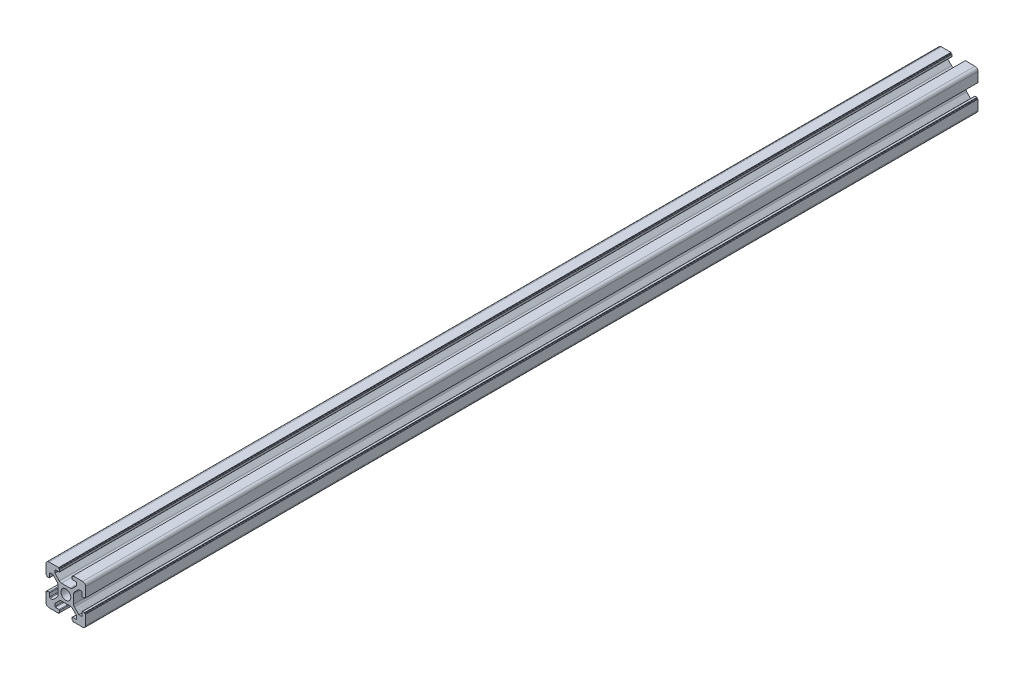
SolidWorks part; units mm, degrees
ref_plane "前视基准面" through (0, 0, 0) normal (0, 0, 1) x (1, 0, 0)
ref_plane "上视基准面" through (0, 0, 0) normal (0, 1, 0) x (1, 0, 0)
ref_plane "右视基准面" through (0, 0, 0) normal (1, 0, 0) x (0, 0, -1)
sketch "草图1" plane through (0, 0, 0) normal (0, 0, 1) x (1, 0, 0)
  line L0 (4.216, 3.2442) -> (6.4367, 5.4649)
  line L1 (6.4367, 5.4649) -> (7.7767, 5.4649)
  line L2 (8.0767, 5.1649) -> (8.0767, 3.3649)
  line L3 (8.3767, 3.0649) -> (9.3767, 3.0649)
  line L4 (9.3767, 3.0649) -> (9.3767, 3.3649)
  line L5 (9.5767, 3.5649) -> (9.8767, 3.5649)
  line L6 (9.8767, 3.5649) -> (9.8767, 8.4649)
  line L7 (8.3767, 9.9649) -> (3.4767, 9.9649)
  line L8 (3.4767, 9.9649) -> (3.4767, 9.6649)
  line L9 (3.2767, 9.4649) -> (2.9767, 9.4649)
  line L10 (2.9767, 9.4649) -> (2.9767, 8.4649)
  line L11 (3.2767, 8.1649) -> (5.0767, 8.1649)
  line L12 (5.3767, 7.8649) -> (5.3767, 6.5249)
  line L13 (5.3767, 6.5249) -> (3.156, 4.3042)
  line L14 (2.0953, 3.8649) -> (-2.342, 3.8649)
  line L15 (-3.4027, 4.3042) -> (-5.6233, 6.5249)
  line L16 (-5.6233, 6.5249) -> (-5.6233, 7.8649)
  line L17 (-5.3233, 8.1649) -> (-3.5233, 8.1649)
  line L18 (-3.2233, 8.4649) -> (-3.2233, 9.4649)
  line L19 (-3.2233, 9.4649) -> (-3.5233, 9.4649)
  line L20 (-3.7233, 9.6649) -> (-3.7233, 9.9649)
  line L21 (-3.7233, 9.9649) -> (-8.6233, 9.9649)
  line L22 (-10.1233, 8.4649) -> (-10.1233, 3.5649)
  line L23 (-10.1233, 3.5649) -> (-9.8233, 3.5649)
  line L24 (-9.6233, 3.3649) -> (-9.6233, 3.0649)
  line L25 (-9.6233, 3.0649) -> (-8.6233, 3.0649)
  line L26 (-8.3233, 3.3649) -> (-8.3233, 5.1649)
  line L27 (-8.0233, 5.4649) -> (-6.6833, 5.4649)
  line L28 (-6.6833, 5.4649) -> (-4.4627, 3.2442)
  line L29 (-4.0233, 2.1836) -> (-4.0233, -2.2538)
  line L30 (-4.4627, -3.3144) -> (-6.6833, -5.5351)
  line L31 (-6.6833, -5.5351) -> (-8.0233, -5.5351)
  line L32 (-8.3233, -5.2351) -> (-8.3233, -3.4351)
  line L33 (-8.6233, -3.1351) -> (-9.6233, -3.1351)
  line L34 (-9.6233, -3.1351) -> (-9.6233, -3.4351)
  line L35 (-9.8233, -3.6351) -> (-10.1233, -3.6351)
  line L36 (-10.1233, -3.6351) -> (-10.1233, -8.5351)
  line L37 (-8.6233, -10.0351) -> (-3.7233, -10.0351)
  line L38 (-3.7233, -10.0351) -> (-3.7233, -9.7351)
  line L39 (-3.5233, -9.5351) -> (-3.2233, -9.5351)
  line L40 (-3.2233, -9.5351) -> (-3.2233, -8.5351)
  line L41 (-3.5233, -8.2351) -> (-5.3233, -8.2351)
  line L42 (-5.6233, -7.9351) -> (-5.6233, -6.5951)
  line L43 (-5.6233, -6.5951) -> (-3.4027, -4.3744)
  line L44 (-2.342, -3.9351) -> (2.0953, -3.9351)
  line L45 (3.156, -4.3744) -> (5.3767, -6.5951)
  line L46 (5.3767, -6.5951) -> (5.3767, -7.9351)
  line L47 (5.0767, -8.2351) -> (3.2767, -8.2351)
  line L48 (2.9767, -8.5351) -> (2.9767, -9.5351)
  line L49 (2.9767, -9.5351) -> (3.2767, -9.5351)
  line L50 (3.4767, -9.7351) -> (3.4767, -10.0351)
  line L51 (3.4767, -10.0351) -> (8.3767, -10.0351)
  line L52 (9.8767, -8.5351) -> (9.8767, -3.6351)
  line L53 (9.8767, -3.6351) -> (9.5767, -3.6351)
  line L54 (9.3767, -3.4351) -> (9.3767, -3.1351)
  line L55 (9.3767, -3.1351) -> (8.3767, -3.1351)
  line L56 (8.0767, -3.4351) -> (8.0767, -5.2351)
  line L57 (7.7767, -5.5351) -> (6.4367, -5.5351)
  line L58 (6.4367, -5.5351) -> (4.216, -3.3144)
  line L59 (3.7767, -2.2538) -> (3.7767, 2.1836)
  circle A0 centre (-0.1233, -0.0351) radius 2.5
  arc A1 (8.0767, 5.1649) -> (7.7767, 5.4649) centre (7.7767, 5.1649) ccw
  arc A2 (8.0767, 3.3649) -> (8.3767, 3.0649) centre (8.3767, 3.3649) ccw
  arc A3 (9.5767, 3.5649) -> (9.3767, 3.3649) centre (9.5767, 3.3649) ccw
  arc A4 (9.8767, 8.4649) -> (8.3767, 9.9649) centre (8.3767, 8.4649) ccw
  arc A5 (3.2767, 9.4649) -> (3.4767, 9.6649) centre (3.2767, 9.6649) ccw
  arc A6 (2.9767, 8.4649) -> (3.2767, 8.1649) centre (3.2767, 8.4649) ccw
  arc A7 (5.3767, 7.8649) -> (5.0767, 8.1649) centre (5.0767, 7.8649) ccw
  arc A8 (2.0953, 3.8649) -> (3.156, 4.3042) centre (2.0953, 5.3649) ccw
  arc A9 (-3.4027, 4.3042) -> (-2.342, 3.8649) centre (-2.342, 5.3649) ccw
  arc A10 (-5.3233, 8.1649) -> (-5.6233, 7.8649) centre (-5.3233, 7.8649) ccw
  arc A11 (-3.5233, 8.1649) -> (-3.2233, 8.4649) centre (-3.5233, 8.4649) ccw
  arc A12 (-3.7233, 9.6649) -> (-3.5233, 9.4649) centre (-3.5233, 9.6649) ccw
  arc A13 (-8.6233, 9.9649) -> (-10.1233, 8.4649) centre (-8.6233, 8.4649) ccw
  arc A14 (-9.6233, 3.3649) -> (-9.8233, 3.5649) centre (-9.8233, 3.3649) ccw
  arc A15 (-8.6233, 3.0649) -> (-8.3233, 3.3649) centre (-8.6233, 3.3649) ccw
  arc A16 (-8.0233, 5.4649) -> (-8.3233, 5.1649) centre (-8.0233, 5.1649) ccw
  arc A17 (-4.0233, 2.1836) -> (-4.4627, 3.2442) centre (-5.5233, 2.1836) ccw
  arc A18 (-4.4627, -3.3144) -> (-4.0233, -2.2538) centre (-5.5233, -2.2538) ccw
  arc A19 (-8.3233, -5.2351) -> (-8.0233, -5.5351) centre (-8.0233, -5.2351) ccw
  arc A20 (-8.3233, -3.4351) -> (-8.6233, -3.1351) centre (-8.6233, -3.4351) ccw
  arc A21 (-9.8233, -3.6351) -> (-9.6233, -3.4351) centre (-9.8233, -3.4351) ccw
  arc A22 (-10.1233, -8.5351) -> (-8.6233, -10.0351) centre (-8.6233, -8.5351) ccw
  arc A23 (-3.5233, -9.5351) -> (-3.7233, -9.7351) centre (-3.5233, -9.7351) ccw
  arc A24 (-3.2233, -8.5351) -> (-3.5233, -8.2351) centre (-3.5233, -8.5351) ccw
  arc A25 (-5.6233, -7.9351) -> (-5.3233, -8.2351) centre (-5.3233, -7.9351) ccw
  arc A26 (-2.342, -3.9351) -> (-3.4027, -4.3744) centre (-2.342, -5.4351) ccw
  arc A27 (3.156, -4.3744) -> (2.0953, -3.9351) centre (2.0953, -5.4351) ccw
  arc A28 (5.0767, -8.2351) -> (5.3767, -7.9351) centre (5.0767, -7.9351) ccw
  arc A29 (3.2767, -8.2351) -> (2.9767, -8.5351) centre (3.2767, -8.5351) ccw
  arc A30 (3.4767, -9.7351) -> (3.2767, -9.5351) centre (3.2767, -9.7351) ccw
  arc A31 (8.3767, -10.0351) -> (9.8767, -8.5351) centre (8.3767, -8.5351) ccw
  arc A32 (9.3767, -3.4351) -> (9.5767, -3.6351) centre (9.5767, -3.4351) ccw
  arc A33 (8.3767, -3.1351) -> (8.0767, -3.4351) centre (8.3767, -3.4351) ccw
  arc A34 (7.7767, -5.5351) -> (8.0767, -5.2351) centre (7.7767, -5.2351) ccw
  arc A35 (3.7767, -2.2538) -> (4.216, -3.3144) centre (5.2767, -2.2538) ccw
  arc A36 (4.216, 3.2442) -> (3.7767, 2.1836) centre (5.2767, 2.1836) ccw
extrude "凸台-拉伸1" add sketch "草图1" along normal blind 450
